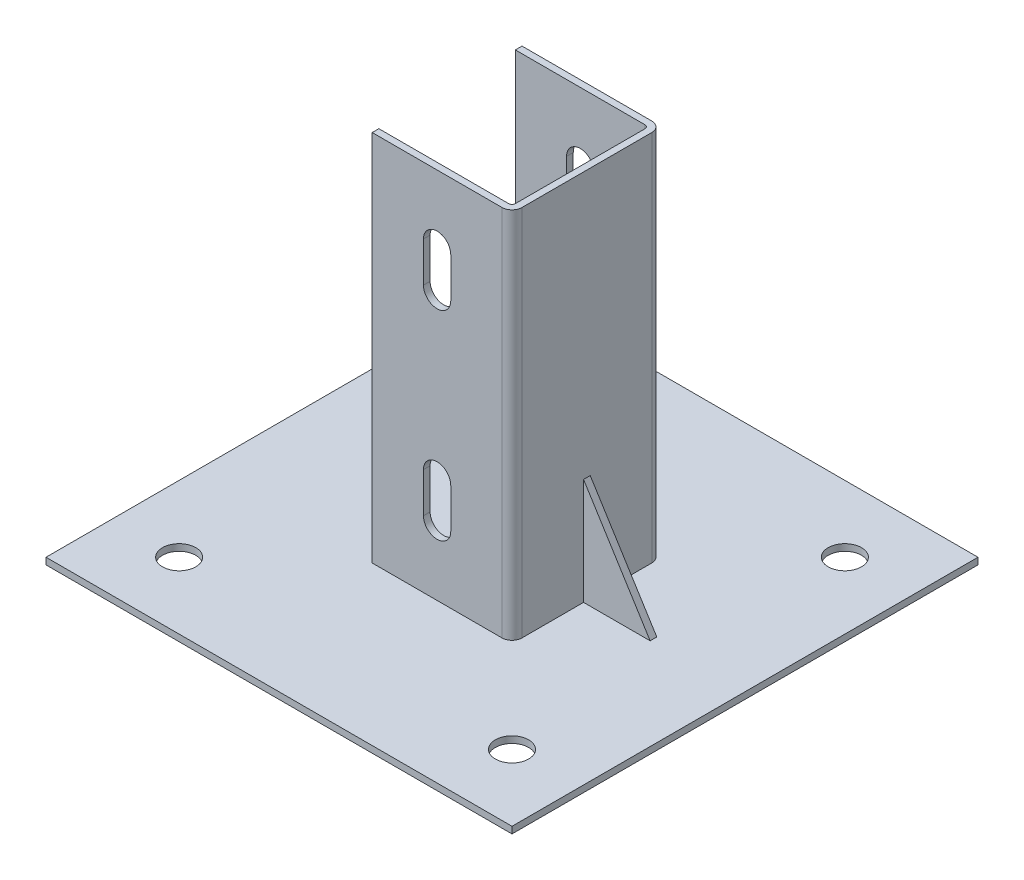
SolidWorks part; units mm, degrees
ref_plane "前视基准面" through (0, 0, 0) normal (0, 0, 1) x (1, 0, 0)
ref_plane "上视基准面" through (0, 0, 0) normal (0, 1, 0) x (1, 0, 0)
ref_plane "右视基准面" through (0, 0, 0) normal (1, 0, 0) x (0, 0, -1)
sketch "草图1" plane through (0, 0, 0) normal (0, 1, 0) x (1, 0, 0)
  line B0 (-19.5, -20.5) -> (19.5, -20.5)
  line B1 (20.5, -19.5) -> (20.5, 19.5)
  line B2 (19.5, 20.5) -> (-19.5, 20.5)
  line B3 (-20.5, 19.5) -> (-20.5, -19.5)
  line B4 (-19.5, -22.5) -> (19.5, -22.5)
  line B5 (22.5, -19.5) -> (22.5, 19.5)
  line B6 (19.5, 22.5) -> (-19.5, 22.5)
  line B7 (-22.5, 19.5) -> (-22.5, -19.5)
  arc B8 (19.5, -20.5) -> (20.5, -19.5) centre (19.5, -19.5) ccw
  arc B9 (20.5, 19.5) -> (19.5, 20.5) centre (19.5, 19.5) ccw
  arc B10 (-19.5, 20.5) -> (-20.5, 19.5) centre (-19.5, 19.5) ccw
  arc B11 (-20.5, -19.5) -> (-19.5, -20.5) centre (-19.5, -19.5) ccw
  arc B12 (19.5, -22.5) -> (22.5, -19.5) centre (19.5, -19.5) ccw
  arc B13 (22.5, 19.5) -> (19.5, 22.5) centre (19.5, 19.5) ccw
  arc B14 (-19.5, 22.5) -> (-22.5, 19.5) centre (-19.5, 19.5) ccw
  arc B15 (-22.5, -19.5) -> (-19.5, -22.5) centre (-19.5, -19.5) ccw
sketch_block_instance "A$C641E5DAA-1"
sketch_block "A$C641E5DAA"
extrude "凸台-拉伸1" add sketch "草图1" along normal blind 112
sketch "草图3" plane through (0, 0, 0) normal (0, -1, 0) x (1, 0, 0)
  line L0 (0, 22.5) -> (0, 26.8861) construction
  line L1 (-70, -70) -> (70, -70)
  line L2 (-70, -70) -> (-70, 70)
  line L3 (-70, 70) -> (70, 70)
  line L4 (70, -70) -> (70, 70)
  line L5 (-19.5, 22.5) -> (19.5, 22.5) construction
  line L6 (-22.5, 0) -> (-12.951, 0) construction
  line L7 (-22.5, -19.5) -> (-22.5, 19.5) construction
  dimension "D1" = 70
  dimension "D2" = 70
  dimension "D3" = 70
  dimension "D4" = 70
extrude "凸台-拉伸2" add sketch "草图3" along normal blind 2
sketch "草图4" plane through (0, 0, 0) normal (0, 0, 1) x (1, 0, 0)
  line L0 (22.5, 32) -> (42.5, 0)
  line L1 (22.5, 112) -> (22.5, 0) construction
  line L2 (70, 0) -> (-70, 0) construction
  line L3 (70, -2) -> (-70, -2) construction
  line L4 (42.5, 0) -> (22.5, 0)
  line L5 (22.5, 0) -> (22.5, 32)
  dimension "D1" = 34
  dimension "D2" = 20
extrude "凸台-拉伸3" add sketch "草图4" along normal mid plane 2
sketch "草图5" plane through (0, 0, 0) normal (0, 0, 1) x (1, 0, 0)
  line L0 (0, 0) -> (0, 83.8597) construction
  line L1 (19.5, 112) -> (19.5, 0) construction
pattern_circular "阵列(圆周)1" count 4 over 360 skipping 1, 2, 3 of "凸台-拉伸3"
sketch "草图6" plane through (0, 0, 22.5) normal (0, 0, 1) x (1, 0, 0)
  line L0 (0, 112) -> (0, 36.3872) construction
  line L1 (-19.5, 112) -> (19.5, 112) construction
  line L2 (0, 80) -> (0, 92) construction
  line L3 (-4.1, 80) -> (-4.1, 92)
  line L4 (4.1, 80) -> (4.1, 92)
  line L5 (0, 20) -> (0, 32) construction
  line L6 (-4.1, 20) -> (-4.1, 32)
  line L7 (4.1, 20) -> (4.1, 32)
  arc A0 (-4.1, 80) -> (4.1, 80) centre (0, 80) ccw
  arc A1 (4.1, 92) -> (-4.1, 92) centre (0, 92) ccw
  arc A2 (-4.1, 20) -> (4.1, 20) centre (0, 20) ccw
  arc A3 (4.1, 32) -> (-4.1, 32) centre (0, 32) ccw
  point P7 (0, 86)
  point P15 (0, 26)
  dimension "D2" = 20
  dimension "D1" = 8.2
  dimension "D3" = 12
  dimension "D4" = 2
extrude "切除-拉伸1" cut sketch "草图6" against normal blind 2
pattern_circular "阵列(圆周)2" count 4 over 360 skipping 1 of "切除-拉伸1"
sketch "草图7" plane through (0, 0, 0) normal (0, 1, 0) x (1, 0, 0)
  circle A0 centre (50, 50) radius 5
  circle A1 centre (50, -50) radius 5
  circle A2 centre (-50, -50) radius 5
  circle A3 centre (-50, 50) radius 5
  point P12 (0, 0)
  dimension "D1" = 50
  dimension "D3" = 10
  dimension "D2" = 50
extrude "切除-拉伸2" cut sketch "草图7" against normal through all
sketch "草图8" plane through (0, 112, 0) normal (0, 1, 0) x (1, 0, 0)
  line L1 (-19.5, -22.5) -> (-29.7221, -22.5)
  line L2 (-19.5, -22.5) -> (-19.5, 25.6625)
  line L3 (-19.5, 25.6625) -> (-29.7221, 25.6625)
  line L4 (-29.7221, -22.5) -> (-29.7221, 25.6625)
extrude "切除-拉伸3" cut sketch "草图8" against normal up to surface (112 mm away) up to face at (-50, 0, -45)
